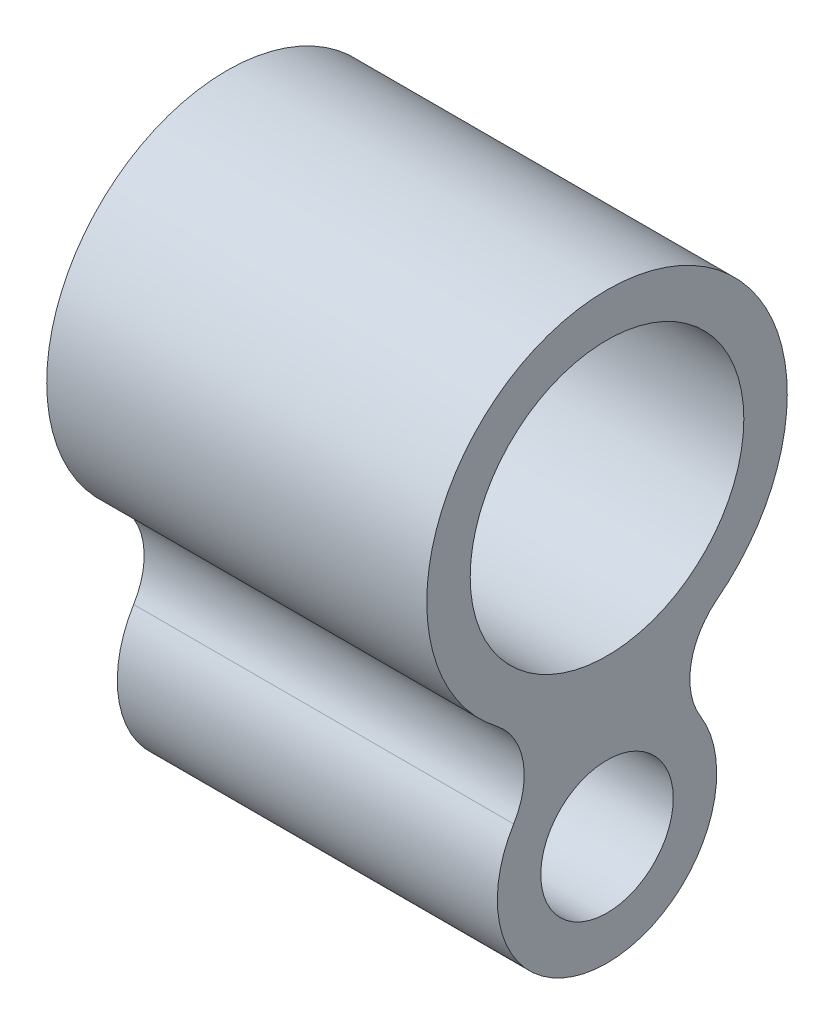
SolidWorks part; units mm, degrees
ref_plane "前视基准面" through (0, 0, 0) normal (0, 0, 1) x (1, 0, 0)
ref_plane "上视基准面" through (0, 0, 0) normal (0, 1, 0) x (1, 0, 0)
ref_plane "右视基准面" through (0, 0, 0) normal (1, 0, 0) x (0, 0, -1)
sketch "草图1" plane through (0, 0, 0) normal (1, 0, 0) x (0, 0, -1)
  line L0 (-10.1, -27) -> (-10.1, -13.1738)
  line L1 (10.1, -27) -> (10.1, -13.1738)
  line L2 (0, 0) -> (0, -27) construction
  circle A0 centre (0, 0) radius 12.6
  arc A1 (10.1, -13.1738) -> (-10.1, -13.1738) centre (0, 0) ccw
  circle A2 centre (0, -27) radius 6.1
  arc A3 (-10.1, -27) -> (10.1, -27) centre (0, -27) ccw
  dimension "D1" = 25.2
  dimension "D2" = 4
  dimension "D3" = 12.2
  dimension "D4" = 4
  dimension "D5" = 27
extrude "凸台-拉伸1" add sketch "草图1" along normal blind 35
sketch "草图3" plane through (35, 0, 0) normal (1, 0, 0) x (0, 0, -1)
  line L0 (0, 0) -> (0, -27) construction
  line L1 (-16.6282, -24.2896) -> (-10.1, -27)
  line L2 (10.1, -27) -> (14.3955, -24.7817)
  circle A0 centre (0, -27) radius 6.1 construction
  arc A1 (-8.5957, -21.6968) -> (-16.6282, -24.2896) centre (-14.1332, -18.2803) ccw
  arc A2 (10.1, -13.1738) -> (-10.1, -13.1738) centre (0, 0) ccw construction
  arc A3 (-10.1, -27) -> (10.1, -27) centre (0, -27) ccw construction
  arc A4 (10.1, -27) -> (8.5957, -21.6968) centre (0, -27) ccw
  arc A5 (8.5957, -21.6968) -> (14.3955, -24.7817) centre (14.1332, -18.2803) cw
  arc A6 (-8.5957, -21.6968) -> (-10.1, -27) centre (0, -27) ccw
extrude "切除-拉伸1" cut sketch "草图3" against normal through all both and the other way through all
